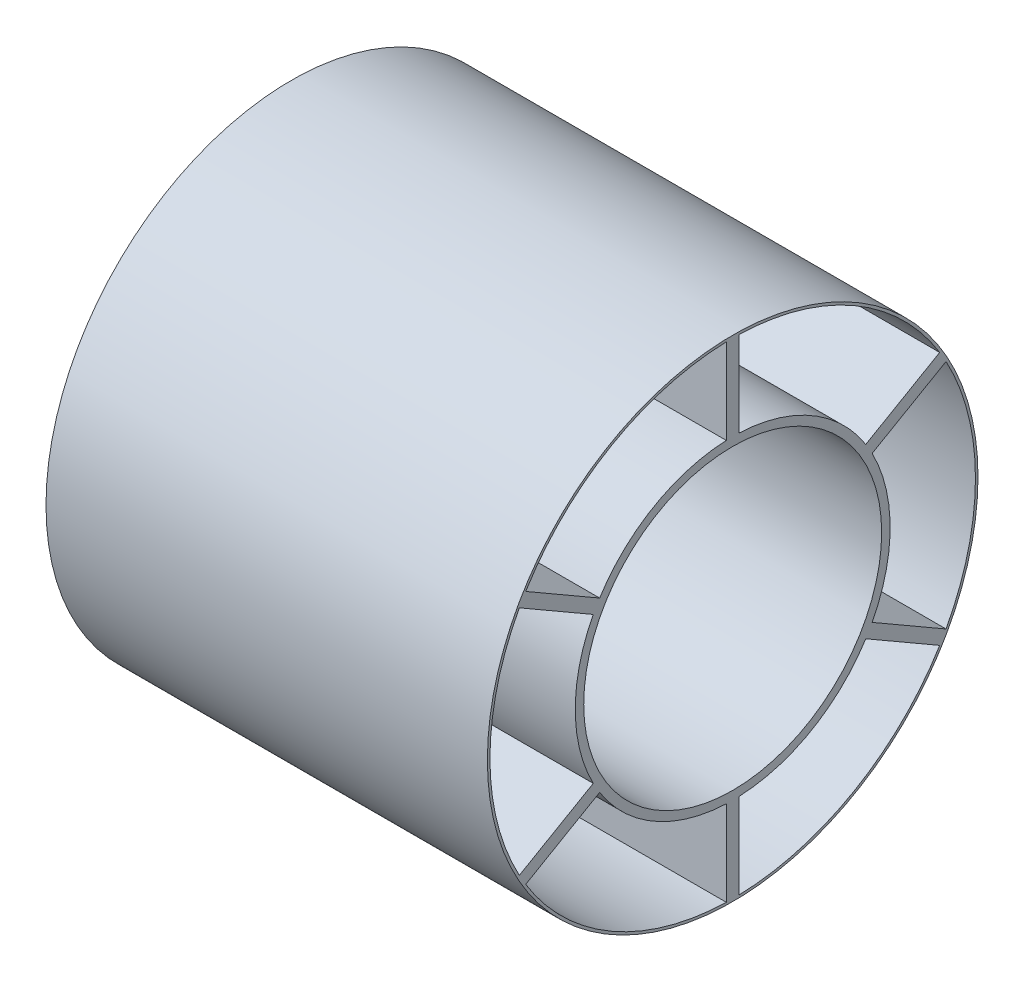
SolidWorks part; units mm, degrees
ref_plane "Alzado" through (0, 0, 0) normal (0, 0, 1) x (1, 0, 0)
ref_plane "Planta" through (0, 0, 0) normal (0, 1, 0) x (1, 0, 0)
ref_plane "Vista lateral" through (0, 0, 0) normal (1, 0, 0) x (0, 0, -1)
sketch "Croquis1" plane through (0, 0, 0) normal (1, 0, 0) x (0, 0, -1)
  circle A0 centre (0, 0) radius 28.6
  circle A1 centre (0, 0) radius 28.9
  dimension "D1" = 57.2
  dimension "D2" = 57.8
extrude "Saliente-Extruir1" add sketch "Croquis1" along normal blind 52
sketch "Croquis2" plane through (0, 0, 0) normal (-1, 0, 0) x (0, 0, 1)
  line L18 (-15.6766, 9.9169) -> (-25.3601, 15.5077)
  line L19 (-16.4266, 8.6179) -> (-26.1101, 14.2086)
  line L20 (-0.75, 18.5348) -> (-0.75, 29.7163)
  line L21 (0.75, 18.5348) -> (0.75, 29.7163)
  line L22 (15.6766, 9.9169) -> (25.3601, 15.5077)
  line L23 (16.4266, 8.6179) -> (26.1101, 14.2086)
  line L26 (16.4266, -8.6179) -> (26.1101, -14.2086)
  line L27 (15.6766, -9.9169) -> (25.3601, -15.5077)
  line L29 (-0.75, -18.5348) -> (-0.75, -29.7163)
  line L30 (0.75, -18.5348) -> (0.75, -29.7163)
  line L31 (-15.6766, -9.9169) -> (-25.3601, -15.5077)
  line L32 (-16.4266, -8.6179) -> (-26.1101, -14.2086)
  arc A0 (0.75, 29.7163) -> (-0.75, 29.7163) centre (0, 0) ccw
  arc A1 (26.1101, 14.2086) -> (25.3601, 15.5077) centre (0, 0) ccw
  arc A2 (25.3601, -15.5077) -> (26.1101, -14.2086) centre (0, 0) ccw
  arc A3 (-0.75, -29.7163) -> (0.75, -29.7163) centre (0, 0) ccw
  arc A4 (-26.1101, -14.2086) -> (-25.3601, -15.5077) centre (0, 0) ccw
  arc A5 (-25.3601, 15.5077) -> (-26.1101, 14.2086) centre (0, 0) ccw
  circle A6 centre (0, 0) radius 17.55
  arc A7 (-16.4266, 8.6179) -> (-16.4266, -8.6179) centre (0, 0) ccw
  arc A8 (-0.75, 18.5348) -> (-15.6766, 9.9169) centre (0, 0) ccw
  arc A9 (15.6766, 9.9169) -> (0.75, 18.5348) centre (0, 0) ccw
  arc A10 (16.4266, -8.6179) -> (16.4266, 8.6179) centre (0, 0) ccw
  arc A11 (0.75, -18.5348) -> (15.6766, -9.9169) centre (0, 0) ccw
  arc A12 (-15.6766, -9.9169) -> (-0.75, -18.5348) centre (0, 0) ccw
  point P5 (0, 0)
  dimension "D2" = 59.4516
  dimension "D4" = 35.1
  dimension "D5" = 37.1
  dimension "D7" = 9.6835
  dimension "D13" = 1.5
  dimension "D1" = 16.4266
  dimension "D3" = 14.2086
  dimension "D6" = 11.1815
  dimension "D8" = 0.75
  dimension "D9" = 18.5348
  dimension "D10" = 1.5
  dimension "D11" = 0.75
  dimension "D12" = 0.75
  dimension "D14" = 0.75
  dimension "D15" = 9.9169
  dimension "D16" = 14.2086
  dimension "D17" = 9.9169
  dimension "D18" = 0.75
  dimension "D19" = 8.6179
  dimension "D20" = 29.7258
  dimension "D21" = 14.2086
  dimension "D22" = 0.75
  dimension "D23" = 18.5348
  dimension "D24" = 29.7163
  dimension "D25" = 11.1815
  dimension "D26" = 0.75
  dimension "D27" = 25.3601
  dimension "D28" = 15.6766
  dimension "D29" = 14.2086
  dimension "D30" = 8.6179
extrude "Saliente-Extruir2" add sketch "Croquis2" against normal up to surface (52 mm away) up to face at (52, 0, -28.9)
sketch "Croquis3" plane through (0, 0, 0) normal (-1, 0, 0) x (0, 0, 1)
  circle A0 centre (0, 0) radius 17.55
  circle A1 centre (0, 0) radius 15
  dimension "D1" = 35.1
  dimension "D2" = 30
extrude "Saliente-Extruir3" add sketch "Croquis3" against normal blind 2
sketch "Croquis4" plane through (52, 0, 0) normal (1, 0, 0) x (0, 0, -1)
  circle A0 centre (0, 0) radius 28.9
extrude "Cortar-Extruir1" cut sketch "Croquis4" against normal blind 100 flip side to cut
